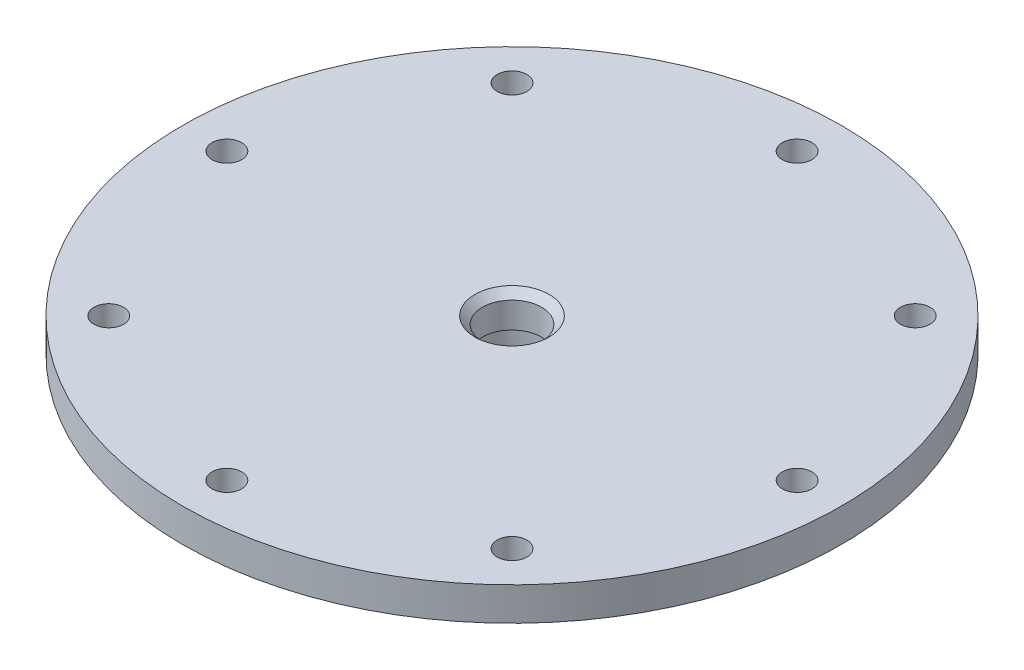
SolidWorks part; units mm, degrees
ref_plane "Спереди" through (0, 0, 0) normal (0, 0, 1) x (1, 0, 0)
ref_plane "Сверху" through (0, 0, 0) normal (0, 1, 0) x (1, 0, 0)
ref_plane "Справа" through (0, 0, 0) normal (1, 0, 0) x (0, 0, -1)
sketch "Эскиз1" plane through (0, 0, 0) normal (0, 1, 0) x (1, 0, 0)
  circle A0 centre (0, 0) radius 22.25
  circle A1 centre (0, 0) radius 2
extrude "Вытянуть1" add sketch "Эскиз1" along normal blind 2.25
sketch "Эскиз3" plane through (0, 0, 0) normal (0, -1, 0) x (1, 0, 0)
  circle A0 centre (0, 0) radius 2.5
  circle A1 centre (0, 0) radius 3.65
extrude "Вытянуть2" add sketch "Эскиз3" along normal blind 3
chamfer "Фаска1" distance 0.5 angle 45 1 edges at (0, 2.25, 2)
sketch "Эскиз4" plane through (0, 2.25, 0) normal (0, 1, 0) x (1, 0, 0)
  line L0 (0, 0) -> (0, 23.6084) construction
  line L1 (0, 22.25) -> (18.2726, 22.25) construction
  circle A0 centre (0, 19.25) radius 1
  circle A2 centre (13.6118, 13.6118) radius 1
  circle A3 centre (19.25, 0) radius 1
  circle A4 centre (13.6118, -13.6118) radius 1
  circle A5 centre (0, -19.25) radius 1
  circle A6 centre (-13.6118, -13.6118) radius 1
  circle A7 centre (-19.25, 0) radius 1
  circle A8 centre (-13.6118, 13.6118) radius 1
  dimension "D1" = 3
extrude "Вытянуть3" cut sketch "Эскиз4" against normal through all
